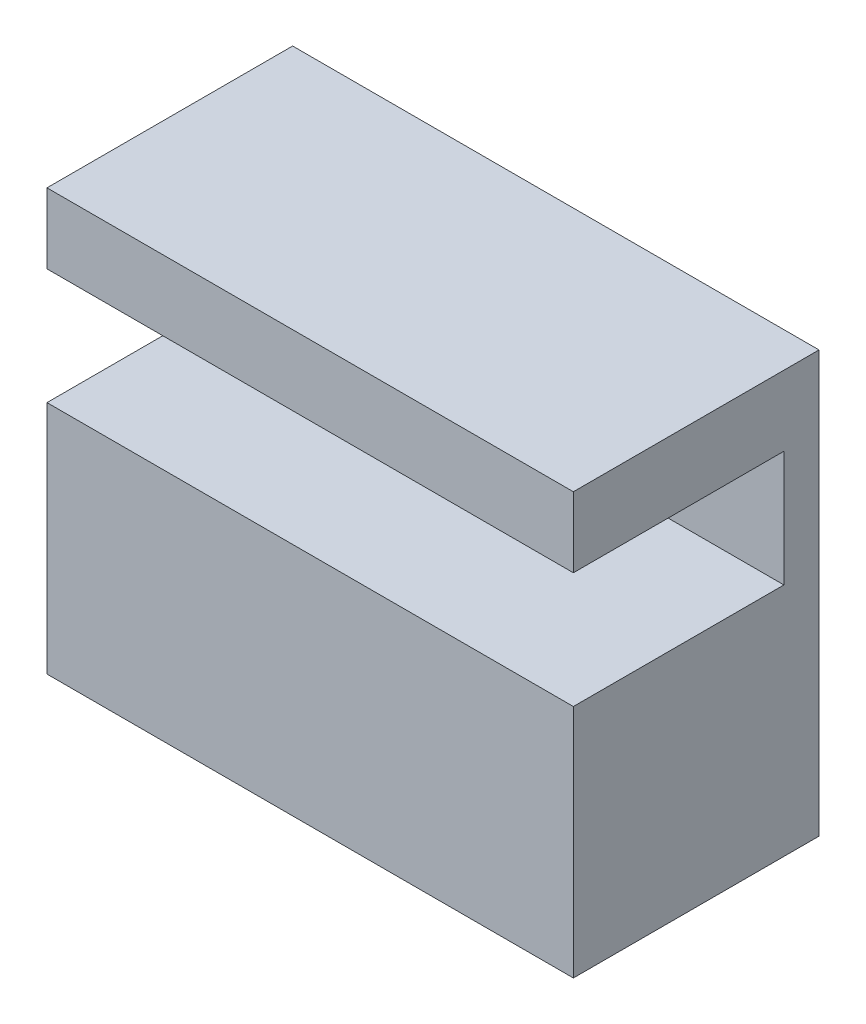
SolidWorks part; units mm, degrees
ref_plane "前视基准面" through (0, 0, 0) normal (0, 0, 1) x (1, 0, 0)
ref_plane "上视基准面" through (0, 0, 0) normal (0, 1, 0) x (1, 0, 0)
ref_plane "右视基准面" through (0, 0, 0) normal (1, 0, 0) x (0, 0, -1)
sketch "草图1" plane through (0, 0, 0) normal (0, 0, 1) x (1, 0, 0)
  line L1 (-7.5, 6) -> (7.5, 6)
  line L2 (-7.5, 6) -> (-7.5, -6)
  line L3 (-7.5, -6) -> (7.5, -6)
  line L4 (7.5, 6) -> (7.5, -6)
  line L5 (-7.5, 6) -> (7.5, -6) construction
  line L6 (-7.5, -6) -> (7.5, 6) construction
  point P0 (0, 0)
  dimension "D1" = 15
  dimension "D2" = 12
extrude "凸台-拉伸1" add sketch "草图1" along normal blind 7
sketch "草图2" plane through (0, 0, 7) normal (0, 0, 1) x (1, 0, 0)
  line L0 (-7.5, 6) -> (-7.5, -6) construction
  line L2 (-7.5, 6) -> (-7.5, 4)
  line L5 (7.5, 6) -> (-7.5, 6) construction
  line L8 (-7.5, 0.7) -> (7.5, 0.7)
  line L13 (-7.5, 4) -> (7.5, 4)
  line L14 (-7.5, 4) -> (-7.5, 0.7)
  line L15 (-7.5, 0.7) -> (7.5, 0.7)
  line L16 (7.5, 4) -> (7.5, 0.7)
  line M10 (7.5, -6) -> (7.5, 6)
  line M12 (-7.5, 6) -> (-7.5, -6)
  dimension "D1" = 2
  dimension "D2" = 3.3
extrude "切除-拉伸1" cut sketch "草图2" against normal blind 6 contours L13 L8 M12 M10
